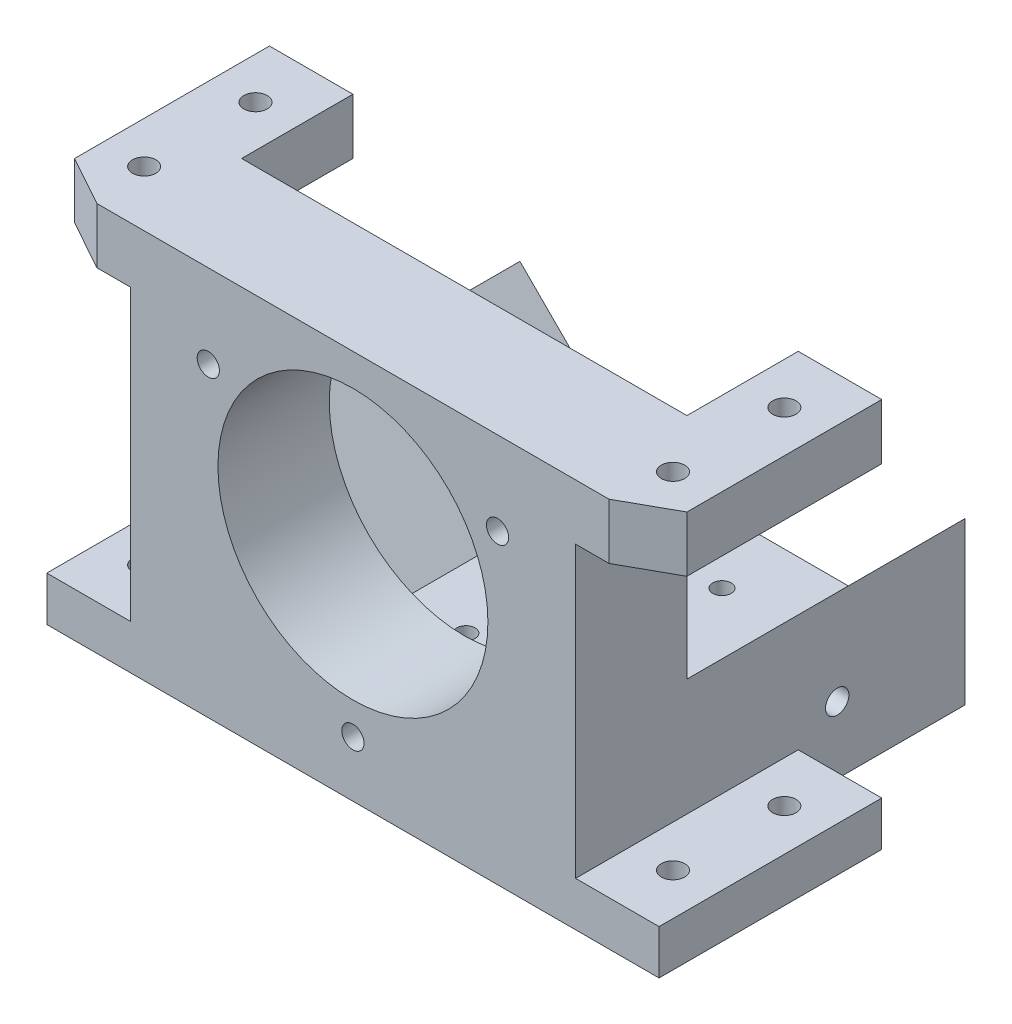
SolidWorks part; units mm, degrees
ref_plane "Front Plane" through (0, 0, 0) normal (0, 0, 1) x (1, 0, 0)
ref_plane "Top Plane" through (0, 0, 0) normal (0, 1, 0) x (1, 0, 0)
ref_plane "Right Plane" through (0, 0, 0) normal (1, 0, 0) x (0, 0, -1)
sketch "Sketch1" plane through (0, 0, 0) normal (0, 0, 1) x (1, 0, 0)
  line L1 (-40, -30) -> (40, -30)
  line L2 (-40, -30) -> (-40, 30)
  line L3 (-40, 30) -> (40, 30)
  line L4 (40, -30) -> (40, 30)
  line L5 (-40, -30) -> (40, 30) construction
  line L6 (-40, 30) -> (40, -30) construction
  circle A0 centre (0, 0) radius 24.25
  dimension "D1" = 48.5
  dimension "D2" = 80
  dimension "D3" = 60
extrude "Boss-Extrude1" add sketch "Sketch1" along normal blind 20
sketch "Sketch4" plane through (40, 0, 0) normal (1, 0, 0) x (0, 0, -1)
  line L0 (0, -30) -> (0, 30) construction
  line L1 (-20, 30) -> (0, 30)
  line L2 (-20, 30) -> (-20, 20)
  line L3 (-20, 20) -> (0, 20)
  line L5 (-20, 30) -> (0, 20) construction
  line L6 (-20, 20) -> (0, 30) construction
  line L8 (0, 30) -> (20, 30)
  line L10 (0, 20) -> (20, 20)
  line L11 (20, 30) -> (20, 20)
  line L12 (0, 30) -> (20, 20) construction
  line L13 (0, 20) -> (20, 30) construction
  point P4 (-10, 25)
  point P10 (10, 25)
  dimension "D1" = 10
extrude "Boss-Extrude3" add sketch "Sketch4" along normal blind 15
sketch "Sketch5" plane through (0, 30, 0) normal (0, 1, 0) x (1, 0, 0)
  line L0 (-40, -10) -> (55, -10) construction
  line L1 (55, 20) -> (55, -20) construction
  line L2 (46, -20) -> (55, -15)
  line L3 (40, 0) -> (40, -20) construction
  line L4 (40, 0) -> (-40, 0) construction
  line L5 (55, -20) -> (-40, -20) construction
  line L6 (-40, -20) -> (-40, 0) construction
  line L7 (55, 20) -> (55, -20) construction
  line L8 (40, 0) -> (55, 0) construction
  line L9 (55, -15) -> (55, -20)
  line L10 (55, -20) -> (46, -20)
  circle A0 centre (47.5, -10) radius 2.1
  circle A1 centre (47.5, 10) radius 2.1
  dimension "D1" = 4.2
  dimension "D2" = 7.5
  dimension "D3" = 9
  dimension "D4" = 5
extrude "Cut-Extrude2" cut sketch "Sketch5" against normal up to surface (10 mm away) up to face at (46, 20, 0)
sketch "Sketch6" plane through (0, -30, 0) normal (0, -1, 0) x (-1, 0, 0)
  line L1 (40, -20) -> (-40, -20)
  line L2 (40, -20) -> (40, 0)
  line L3 (40, 0) -> (-40, 0)
  line L4 (-40, -20) -> (-40, 0)
  line L5 (40, -20) -> (-40, 0) construction
  line L6 (40, 0) -> (-40, -20) construction
  point P4 (0, -10)
extrude "Boss-Extrude4" add sketch "Sketch6" along normal blind 2
sketch "Sketch8" plane through (0, 0, 0) normal (0, 0, -1) x (-1, 0, 0)
  line L0 (-40, -11) -> (-19, -32)
  line L1 (-40, -32) -> (-40, 20) construction
  line L2 (40, -32) -> (-40, -32) construction
  line L3 (-19, -32) -> (-40, -32)
  line L4 (-40, -32) -> (-40, -11)
  dimension "D1" = 21
extrude "Boss-Extrude6" add sketch "Sketch8" along normal blind 50
sketch "Sketch9" plane through (40, 0, 0) normal (1, 0, 0) x (0, 0, -1)
  line L0 (-20, -32) -> (-20, 20) construction
  line L1 (50, -32) -> (-20, -32) construction
  circle A0 centre (27, -28) radius 2.1
  dimension "D1" = 4.2
  dimension "D2" = 47
  dimension "D3" = 4
extrude "Cut-Extrude3" cut sketch "Sketch9" against normal through all
ref_plane "Plane1" through (19, 0, 0) normal (-1, 0, 0) x (0, 0, 1)
sketch "Sketch12" plane through (0, -32, 0) normal (0, -1, 0) x (1, 0, 0)
  line L0 (0, 20) -> (0, -50) construction
  line L1 (-40, 20) -> (40, 20)
  line L2 (-40, 20) -> (-40, -50)
  line L3 (-40, -50) -> (40, -50)
  line L4 (40, 20) -> (40, -50)
  line L5 (-40, 20) -> (40, -50) construction
  line L6 (-40, -50) -> (40, 20) construction
  line L7 (-8, -8.3) -> (8, -8.3) construction
  line L8 (-8, -8.3) -> (-8, -38.3) construction
  line L9 (-8, -38.3) -> (8, -38.3) construction
  line L10 (8, -38.3) -> (8, -8.3) construction
  line L11 (-40, 0) -> (19, 0) construction
  circle A0 centre (-8, -8.3) radius 1.65
  circle A1 centre (8, -8.3) radius 1.65
  circle A2 centre (8, -38.3) radius 1.65
  circle A3 centre (-8, -38.3) radius 1.65
  point P4 (0, -15)
  point P11 (0, -8.3)
  dimension "D4" = 3.3
  dimension "D1" = 16
  dimension "D2" = 30
  dimension "D3" = 8.3
extrude "Boss-Extrude8" add sketch "Sketch12" along normal blind 8
ref_plane "Plane2" through (0, 0, 0) normal (1, 0, 0) x (0, 0, -1)
mirror "Mirror1" about plane through (0, 0, 0) normal (1, 0, 0) of "Cut-Extrude3", "Boss-Extrude6", "Boss-Extrude4", "Cut-Extrude2", "Boss-Extrude3"
sketch "Sketch13" plane through (-40, 0, 0) normal (-1, 0, 0) x (0, 0, 1)
  line L0 (20, 20) -> (20, -40) construction
  line L1 (20, -40) -> (0, -40)
  line L2 (20, -40) -> (20, -32)
  line L3 (20, -32) -> (0, -32)
  line L5 (20, -40) -> (0, -32) construction
  line L6 (20, -32) -> (0, -40) construction
  line L7 (15, 20) -> (-20, 20) construction
  line L13 (-20, -40) -> (0, -40)
  line L14 (-20, -40) -> (-20, -32)
  line L15 (-20, -32) -> (0, -32)
  line L17 (-20, -40) -> (0, -32) construction
  line L18 (-20, -32) -> (0, -40) construction
  point P4 (10, -36)
  point P15 (-10, -36)
  dimension "D1" = 8
  dimension "D2" = 52
  dimension "D3" = 20
extrude "Boss-Extrude9" add sketch "Sketch13" along normal blind 15
sketch "Sketch14" plane through (0, -40, 0) normal (0, -1, 0) x (1, 0, 0)
  line L0 (-55, 0) -> (-27.8806, 0) construction
  line L1 (-55, -20) -> (-55, 20) construction
  circle A0 centre (-47.5, 10) radius 2.1
  circle A1 centre (-47.5, 10) radius 2.1 construction
  circle A2 centre (-47.5, -10) radius 2.1
extrude "Cut-Extrude4" cut sketch "Sketch14" against normal blind 10
mirror "Mirror2" about plane through (0, 0, 0) normal (1, 0, 0) of "Cut-Extrude4", "Boss-Extrude9"
sketch "Sketch15" plane through (0, -40, 0) normal (0, -1, 0) x (1, 0, 0)
  line L0 (-8, -8.3) -> (8, -8.3) construction
  line L1 (-55, 20) -> (55, 20)
  line L2 (-55, 20) -> (-55, -20)
  line L3 (-55, -20) -> (55, -20)
  line L4 (55, 20) -> (55, -20)
  line L5 (-55, 20) -> (55, -20) construction
  line L6 (-55, -20) -> (55, 20) construction
  line L7 (-8, -3.3) -> (8, -3.3)
  line L8 (-8, -13.3) -> (8, -13.3)
  circle A0 centre (-47.5, 10) radius 2.1
  circle A1 centre (-47.5, -10) radius 2.0834
  circle A2 centre (47.5, -10) radius 2
  circle A3 centre (47.5, 10) radius 2
  circle A4 centre (-47.5, 10) radius 2.1 construction
  arc A24 (-8, -3.3) -> (-8, -13.3) centre (-8, -8.3) ccw
  arc A25 (8, -13.3) -> (8, -3.3) centre (8, -8.3) ccw
  circle A26 centre (8, -8.3) radius 1.65 construction
  point P4 (0, 0)
  point P19 (0, -8.3)
  point P24 (13, -8.3)
  dimension "D1" = 5
sketch "Sketch16" plane through (0, 0, 20) normal (0, 0, 1) x (1, 0, 0)
  line L0 (0, -34.1) -> (0, 34.1) construction
  line L1 (0, -30) -> (0, -24.25) construction
  line L2 (0, 0) -> (0, -30) construction
  circle A0 centre (0, -30) radius 2
  circle A1 centre (0, 0) radius 24.25 construction
  dimension "D1" = 4
  dimension "D2" = 30
extrude "Cut-Extrude5" cut sketch "Sketch16" against normal blind 3
pattern_circular "CirPattern1" count 3 every 120 about axis through (0, 0, 0) along (0, 0, 1) of "Cut-Extrude5"
